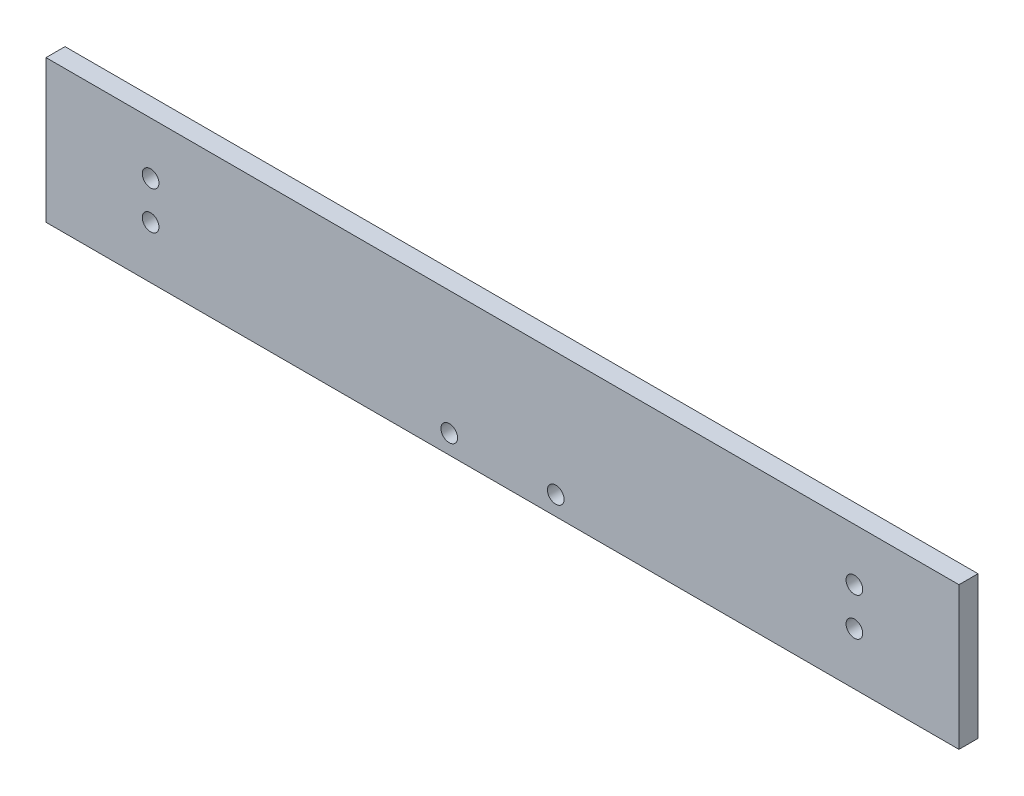
SolidWorks part; units mm, degrees
ref_plane "정면" through (0, 0, 0) normal (0, 0, 1) x (1, 0, 0)
ref_plane "윗면" through (0, 0, 0) normal (0, 1, 0) x (1, 0, 0)
ref_plane "우측면" through (0, 0, 0) normal (1, 0, 0) x (0, 0, -1)
sketch "스케치1" plane through (0, 0, 0) normal (0, 0, 1) x (1, 0, 0)
  line L0 (0, 1049.4319) -> (0, -1141.9887) construction
  line L1 (-91.3948, -16.7612) -> (100.6052, -16.7612)
  line L2 (100.6052, -16.7612) -> (100.6052, 13.2388)
  line L3 (100.6052, 13.2388) -> (-91.3948, 13.2388)
  line L4 (-91.3948, -16.7612) -> (-91.3948, 13.2388)
  line L5 (100.6052, -16.7612) -> (-91.3948, 13.2388) construction
  line L6 (100.6052, 13.2388) -> (-91.3948, -16.7612) construction
  line L7 (-9.8948, -9.7612) -> (19.1052, -9.7612)
  line L8 (-9.8948, -9.7612) -> (-9.8948, -16.7612)
  line L9 (-9.8948, -16.7612) -> (19.1052, -16.7612)
  line L10 (19.1052, -9.7612) -> (19.1052, -16.7612)
  circle A0 centre (78.6052, -5.7612) radius 1.75
  circle A1 centre (78.6052, 2.2388) radius 1.75
  circle A2 centre (-69.3948, -5.7612) radius 1.75
  circle A3 centre (-69.3948, 2.2388) radius 1.75
  circle A4 centre (-6.5948, -12.7612) radius 1.75
  circle A5 centre (15.8052, -12.7612) radius 1.75
  point P3 (4.6052, -1.7612)
  point P8 (78.6052, 2.2388)
  point P9 (78.6052, -5.7612)
  point P22 (-9.8948, -9.7612)
  dimension "D1" = 8
  dimension "D7" = 4
  dimension "D8" = 3
  dimension "D4" = 3.5
  dimension "D5" = 3.5
  dimension "D2" = 11
  dimension "D3" = 22
  dimension "D6" = 192
  dimension "D9" = 3.3
extrude "보스-돌출2" add sketch "스케치1" along normal blind 4 contours L7 L10 L1 L2 L3 L4 L8 A2 A1 A0 A3 | L10 L7 L8 L1 A5 A4
